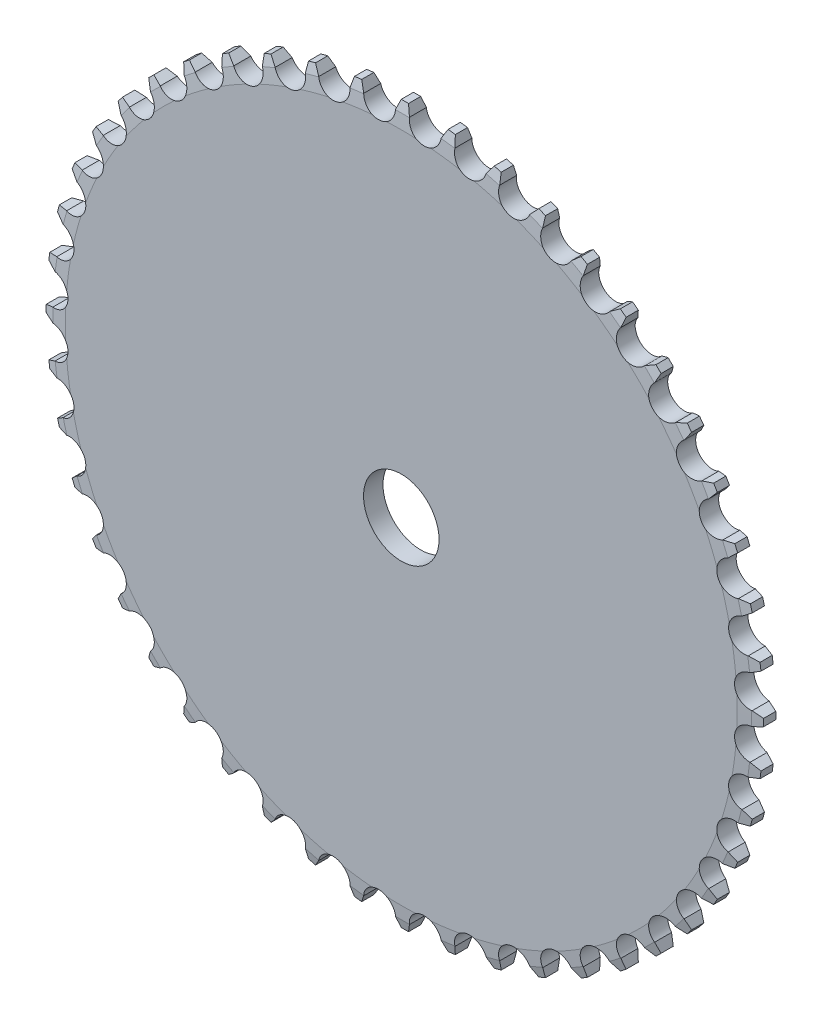
SolidWorks part; units mm, degrees
material "AISI 1045 Steel, cold drawn"
ref_plane "Front Plane" through (0, 0, 0) normal (0, 0, 1) x (1, 0, 0)
ref_plane "Top Plane" through (0, 0, 0) normal (0, 1, 0) x (1, 0, 0)
ref_plane "Right Plane" through (0, 0, 0) normal (1, 0, 0) x (0, 0, -1)
sketch "Sketch1" plane through (0, 0, 0) normal (0, 0, 1) x (1, 0, 0)
  line L0 (0, 0) -> (-4.5942, 70.0933) construction
  line L1 (0, 0) -> (4.5942, 70.0933) construction
  line L2 (0, 0) -> (0, 75.4253) construction
  line L3 (-0.762, 75.4215) -> (0.762, 75.4215)
  line L4 (0.762, 75.4215) -> (1.457, 73.512)
  line L5 (9.089, 74.8757) -> (8.1507, 73.0733)
  line L6 (18.7845, 73.0487) -> (17.619, 71.3842)
  line L7 (10.6, 74.6767) -> (11.0398, 72.6929)
  line L8 (9.089, 74.8757) -> (10.6, 74.6767)
  line L9 (28.1585, 69.9719) -> (26.7857, 68.4738)
  line L10 (20.2565, 72.6543) -> (20.4336, 70.63)
  line L11 (18.7845, 73.0487) -> (20.2565, 72.6543)
  line L12 (37.0508, 65.6979) -> (35.4942, 64.3917)
  line L13 (29.5665, 69.3887) -> (29.4779, 67.3587)
  line L14 (28.1585, 69.9719) -> (29.5665, 69.3887)
  line L15 (45.3091, 60.2997) -> (43.5954, 59.2079)
  line L16 (38.3706, 64.9359) -> (38.0178, 62.9348)
  line L17 (37.0508, 65.6979) -> (38.3706, 64.9359)
  line L18 (52.7922, 53.8698) -> (50.9506, 53.0111)
  line L19 (46.5182, 59.372) -> (45.9072, 57.434)
  line L20 (45.3091, 60.2997) -> (46.5182, 59.372)
  line L21 (59.372, 46.5182) -> (57.434, 45.9072)
  line L22 (53.8698, 52.7922) -> (53.0111, 50.9506)
  line L23 (52.7922, 53.8698) -> (53.8698, 52.7922)
  line L24 (64.9359, 38.3706) -> (62.9348, 38.0178)
  line L25 (60.2997, 45.3091) -> (59.2079, 43.5954)
  line L26 (59.372, 46.5182) -> (60.2997, 45.3091)
  line L27 (69.3887, 29.5665) -> (67.3587, 29.4779)
  line L28 (65.6979, 37.0508) -> (64.3917, 35.4942)
  line L29 (64.9359, 38.3706) -> (65.6979, 37.0508)
  line L30 (72.6543, 20.2565) -> (70.63, 20.4336)
  line L31 (69.9719, 28.1585) -> (68.4738, 26.7857)
  line L32 (69.3887, 29.5665) -> (69.9719, 28.1585)
  line L33 (74.6767, 10.6) -> (72.6929, 11.0398)
  line L34 (73.0487, 18.7845) -> (71.3842, 17.619)
  line L35 (72.6543, 20.2565) -> (73.0487, 18.7845)
  line L36 (75.4215, 0.762) -> (73.512, 1.457)
  line L37 (74.8757, 9.089) -> (73.0733, 8.1507)
  line L38 (74.6767, 10.6) -> (74.8757, 9.089)
  line L39 (74.8757, -9.089) -> (73.0733, -8.1507)
  line L40 (75.4215, -0.762) -> (73.512, -1.457)
  line L41 (75.4215, 0.762) -> (75.4215, -0.762)
  line L42 (73.0487, -18.7845) -> (71.3842, -17.619)
  line L43 (74.6767, -10.6) -> (72.6929, -11.0398)
  line L44 (74.8757, -9.089) -> (74.6767, -10.6)
  line L45 (69.9719, -28.1585) -> (68.4738, -26.7857)
  line L46 (72.6543, -20.2565) -> (70.63, -20.4336)
  line L47 (73.0487, -18.7845) -> (72.6543, -20.2565)
  line L48 (65.6979, -37.0508) -> (64.3917, -35.4942)
  line L49 (69.3887, -29.5665) -> (67.3587, -29.4779)
  line L50 (69.9719, -28.1585) -> (69.3887, -29.5665)
  line L51 (60.2997, -45.3091) -> (59.2079, -43.5954)
  line L52 (64.9359, -38.3706) -> (62.9348, -38.0178)
  line L53 (65.6979, -37.0508) -> (64.9359, -38.3706)
  line L54 (53.8698, -52.7922) -> (53.0111, -50.9506)
  line L55 (59.372, -46.5182) -> (57.434, -45.9072)
  line L56 (60.2997, -45.3091) -> (59.372, -46.5182)
  line L57 (46.5182, -59.372) -> (45.9072, -57.434)
  line L58 (52.7922, -53.8698) -> (50.9506, -53.0111)
  line L59 (53.8698, -52.7922) -> (52.7922, -53.8698)
  line L60 (38.3706, -64.9359) -> (38.0178, -62.9348)
  line L61 (45.3091, -60.2997) -> (43.5954, -59.2079)
  line L62 (46.5182, -59.372) -> (45.3091, -60.2997)
  line L63 (29.5665, -69.3887) -> (29.4779, -67.3587)
  line L64 (37.0508, -65.6979) -> (35.4942, -64.3917)
  line L65 (38.3706, -64.9359) -> (37.0508, -65.6979)
  line L66 (20.2565, -72.6543) -> (20.4336, -70.63)
  line L67 (28.1585, -69.9719) -> (26.7857, -68.4738)
  line L68 (29.5665, -69.3887) -> (28.1585, -69.9719)
  line L69 (10.6, -74.6767) -> (11.0398, -72.6929)
  line L70 (18.7845, -73.0487) -> (17.619, -71.3842)
  line L71 (20.2565, -72.6543) -> (18.7845, -73.0487)
  line L72 (0.762, -75.4215) -> (1.457, -73.512)
  line L73 (9.089, -74.8757) -> (8.1507, -73.0733)
  line L74 (10.6, -74.6767) -> (9.089, -74.8757)
  line L75 (-9.089, -74.8757) -> (-8.1507, -73.0733)
  line L76 (-0.762, -75.4215) -> (-1.457, -73.512)
  line L77 (0.762, -75.4215) -> (-0.762, -75.4215)
  line L78 (-18.7845, -73.0487) -> (-17.619, -71.3842)
  line L79 (-10.6, -74.6767) -> (-11.0398, -72.6929)
  line L80 (-9.089, -74.8757) -> (-10.6, -74.6767)
  line L81 (-28.1585, -69.9719) -> (-26.7857, -68.4738)
  line L82 (-20.2565, -72.6543) -> (-20.4336, -70.63)
  line L83 (-18.7845, -73.0487) -> (-20.2565, -72.6543)
  line L84 (-37.0508, -65.6979) -> (-35.4942, -64.3917)
  line L85 (-29.5665, -69.3887) -> (-29.4779, -67.3587)
  line L86 (-28.1585, -69.9719) -> (-29.5665, -69.3887)
  line L87 (-45.3091, -60.2997) -> (-43.5954, -59.2079)
  line L88 (-38.3706, -64.9359) -> (-38.0178, -62.9348)
  line L89 (-37.0508, -65.6979) -> (-38.3706, -64.9359)
  line L90 (-52.7922, -53.8698) -> (-50.9506, -53.0111)
  line L91 (-46.5182, -59.372) -> (-45.9072, -57.434)
  line L92 (-45.3091, -60.2997) -> (-46.5182, -59.372)
  line L93 (-59.372, -46.5182) -> (-57.434, -45.9072)
  line L94 (-53.8698, -52.7922) -> (-53.0111, -50.9506)
  line L95 (-52.7922, -53.8698) -> (-53.8698, -52.7922)
  line L96 (-64.9359, -38.3706) -> (-62.9348, -38.0178)
  line L97 (-60.2997, -45.3091) -> (-59.2079, -43.5954)
  line L98 (-59.372, -46.5182) -> (-60.2997, -45.3091)
  line L99 (-69.3887, -29.5665) -> (-67.3587, -29.4779)
  line L100 (-65.6979, -37.0508) -> (-64.3917, -35.4942)
  line L101 (-64.9359, -38.3706) -> (-65.6979, -37.0508)
  line L102 (-72.6543, -20.2565) -> (-70.63, -20.4336)
  line L103 (-69.9719, -28.1585) -> (-68.4738, -26.7857)
  line L104 (-69.3887, -29.5665) -> (-69.9719, -28.1585)
  line L105 (-74.6767, -10.6) -> (-72.6929, -11.0398)
  line L106 (-73.0487, -18.7845) -> (-71.3842, -17.619)
  line L107 (-72.6543, -20.2565) -> (-73.0487, -18.7845)
  line L108 (-75.4215, -0.762) -> (-73.512, -1.457)
  line L109 (-74.8757, -9.089) -> (-73.0733, -8.1507)
  line L110 (-74.6767, -10.6) -> (-74.8757, -9.089)
  line L111 (-74.8757, 9.089) -> (-73.0733, 8.1507)
  line L112 (-75.4215, 0.762) -> (-73.512, 1.457)
  line L113 (-75.4215, -0.762) -> (-75.4215, 0.762)
  line L114 (-73.0487, 18.7845) -> (-71.3842, 17.619)
  line L115 (-74.6767, 10.6) -> (-72.6929, 11.0398)
  line L116 (-74.8757, 9.089) -> (-74.6767, 10.6)
  line L117 (-69.9719, 28.1585) -> (-68.4738, 26.7857)
  line L118 (-72.6543, 20.2565) -> (-70.63, 20.4336)
  line L119 (-73.0487, 18.7845) -> (-72.6543, 20.2565)
  line L120 (-65.6979, 37.0508) -> (-64.3917, 35.4942)
  line L121 (-69.3887, 29.5665) -> (-67.3587, 29.4779)
  line L122 (-69.9719, 28.1585) -> (-69.3887, 29.5665)
  line L123 (-60.2997, 45.3091) -> (-59.2079, 43.5954)
  line L124 (-64.9359, 38.3706) -> (-62.9348, 38.0178)
  line L125 (-65.6979, 37.0508) -> (-64.9359, 38.3706)
  line L126 (-53.8698, 52.7922) -> (-53.0111, 50.9506)
  line L127 (-59.372, 46.5182) -> (-57.434, 45.9072)
  line L128 (-60.2997, 45.3091) -> (-59.372, 46.5182)
  line L129 (-46.5182, 59.372) -> (-45.9072, 57.434)
  line L130 (-52.7922, 53.8698) -> (-50.9506, 53.0111)
  line L131 (-53.8698, 52.7922) -> (-52.7922, 53.8698)
  line L132 (-38.3706, 64.9359) -> (-38.0178, 62.9348)
  line L133 (-45.3091, 60.2997) -> (-43.5954, 59.2079)
  line L134 (-46.5182, 59.372) -> (-45.3091, 60.2997)
  line L135 (-29.5665, 69.3887) -> (-29.4779, 67.3587)
  line L136 (-37.0508, 65.6979) -> (-35.4942, 64.3917)
  line L137 (-38.3706, 64.9359) -> (-37.0508, 65.6979)
  line L138 (-20.2565, 72.6543) -> (-20.4336, 70.63)
  line L139 (-28.1585, 69.9719) -> (-26.7857, 68.4738)
  line L140 (-29.5665, 69.3887) -> (-28.1585, 69.9719)
  line L141 (-10.6, 74.6767) -> (-11.0398, 72.6929)
  line L142 (-18.7845, 73.0487) -> (-17.619, 71.3842)
  line L143 (-20.2565, 72.6543) -> (-18.7845, 73.0487)
  line L144 (-0.762, 75.4215) -> (-1.457, 73.512)
  line L145 (-9.089, 74.8757) -> (-8.1507, 73.0733)
  line L146 (-10.6, 74.6767) -> (-9.089, 74.8757)
  circle A0 centre (0, 0) radius 75.4253 construction
  circle A1 centre (0, 0) radius 70.2437 construction
  circle A2 centre (0, 0) radius 7.9375
  circle A3 centre (0, 0) radius 73.5264 construction
  arc A4 (1.457, 73.512) -> (4.5942, 70.0933) centre (4.8137, 73.4436) ccw
  arc A5 (4.5942, 70.0933) -> (8.1507, 73.0733) centre (4.8137, 73.4436) ccw
  arc A6 (13.7039, 68.894) -> (17.619, 71.3842) centre (14.3589, 72.1869) ccw
  arc A7 (11.0398, 72.6929) -> (13.7039, 68.894) centre (14.3589, 72.1869) ccw
  arc A8 (22.5791, 66.5159) -> (26.7857, 68.4738) centre (23.6583, 69.6952) ccw
  arc A9 (20.4336, 70.63) -> (22.5791, 66.5159) centre (23.6583, 69.6952) ccw
  arc A10 (31.068, 62.9997) -> (35.4942, 64.3917) centre (32.553, 66.0109) ccw
  arc A11 (29.4779, 67.3587) -> (31.068, 62.9997) centre (32.553, 66.0109) ccw
  arc A12 (39.0253, 58.4055) -> (43.5954, 59.2079) centre (40.8906, 61.1971) ccw
  arc A13 (38.0178, 62.9348) -> (39.0253, 58.4055) centre (40.8906, 61.1971) ccw
  arc A14 (46.3149, 52.812) -> (50.9506, 53.0111) centre (48.5286, 55.3363) ccw
  arc A15 (45.9072, 57.434) -> (46.3149, 52.812) centre (48.5286, 55.3363) ccw
  arc A16 (52.812, 46.3149) -> (57.434, 45.9072) centre (55.3363, 48.5286) ccw
  arc A17 (53.0111, 50.9506) -> (52.812, 46.3149) centre (55.3363, 48.5286) ccw
  arc A18 (58.4055, 39.0253) -> (62.9348, 38.0178) centre (61.1971, 40.8906) ccw
  arc A19 (59.2079, 43.5954) -> (58.4055, 39.0253) centre (61.1971, 40.8906) ccw
  arc A20 (62.9997, 31.068) -> (67.3587, 29.4779) centre (66.0109, 32.553) ccw
  arc A21 (64.3917, 35.4942) -> (62.9997, 31.068) centre (66.0109, 32.553) ccw
  arc A22 (66.5159, 22.5791) -> (70.63, 20.4336) centre (69.6952, 23.6583) ccw
  arc A23 (68.4738, 26.7857) -> (66.5159, 22.5791) centre (69.6952, 23.6583) ccw
  arc A24 (68.894, 13.7039) -> (72.6929, 11.0398) centre (72.1869, 14.3589) ccw
  arc A25 (71.3842, 17.619) -> (68.894, 13.7039) centre (72.1869, 14.3589) ccw
  arc A26 (70.0933, 4.5942) -> (73.512, 1.457) centre (73.4436, 4.8137) ccw
  arc A27 (73.0733, 8.1507) -> (70.0933, 4.5942) centre (73.4436, 4.8137) ccw
  arc A28 (70.0933, -4.5942) -> (73.0733, -8.1507) centre (73.4436, -4.8137) ccw
  arc A29 (73.512, -1.457) -> (70.0933, -4.5942) centre (73.4436, -4.8137) ccw
  arc A30 (68.894, -13.7039) -> (71.3842, -17.619) centre (72.1869, -14.3589) ccw
  arc A31 (72.6929, -11.0398) -> (68.894, -13.7039) centre (72.1869, -14.3589) ccw
  arc A32 (66.5159, -22.5791) -> (68.4738, -26.7857) centre (69.6952, -23.6583) ccw
  arc A33 (70.63, -20.4336) -> (66.5159, -22.5791) centre (69.6952, -23.6583) ccw
  arc A34 (62.9997, -31.068) -> (64.3917, -35.4942) centre (66.0109, -32.553) ccw
  arc A35 (67.3587, -29.4779) -> (62.9997, -31.068) centre (66.0109, -32.553) ccw
  arc A36 (58.4055, -39.0253) -> (59.2079, -43.5954) centre (61.1971, -40.8906) ccw
  arc A37 (62.9348, -38.0178) -> (58.4055, -39.0253) centre (61.1971, -40.8906) ccw
  arc A38 (52.812, -46.3149) -> (53.0111, -50.9506) centre (55.3363, -48.5286) ccw
  arc A39 (57.434, -45.9072) -> (52.812, -46.3149) centre (55.3363, -48.5286) ccw
  arc A40 (46.3149, -52.812) -> (45.9072, -57.434) centre (48.5286, -55.3363) ccw
  arc A41 (50.9506, -53.0111) -> (46.3149, -52.812) centre (48.5286, -55.3363) ccw
  arc A42 (39.0253, -58.4055) -> (38.0178, -62.9348) centre (40.8906, -61.1971) ccw
  arc A43 (43.5954, -59.2079) -> (39.0253, -58.4055) centre (40.8906, -61.1971) ccw
  arc A44 (31.068, -62.9997) -> (29.4779, -67.3587) centre (32.553, -66.0109) ccw
  arc A45 (35.4942, -64.3917) -> (31.068, -62.9997) centre (32.553, -66.0109) ccw
  arc A46 (22.5791, -66.5159) -> (20.4336, -70.63) centre (23.6583, -69.6952) ccw
  arc A47 (26.7857, -68.4738) -> (22.5791, -66.5159) centre (23.6583, -69.6952) ccw
  arc A48 (13.7039, -68.894) -> (11.0398, -72.6929) centre (14.3589, -72.1869) ccw
  arc A49 (17.619, -71.3842) -> (13.7039, -68.894) centre (14.3589, -72.1869) ccw
  arc A50 (4.5942, -70.0933) -> (1.457, -73.512) centre (4.8137, -73.4436) ccw
  arc A51 (8.1507, -73.0733) -> (4.5942, -70.0933) centre (4.8137, -73.4436) ccw
  arc A52 (-4.5942, -70.0933) -> (-8.1507, -73.0733) centre (-4.8137, -73.4436) ccw
  arc A53 (-1.457, -73.512) -> (-4.5942, -70.0933) centre (-4.8137, -73.4436) ccw
  arc A54 (-13.7039, -68.894) -> (-17.619, -71.3842) centre (-14.3589, -72.1869) ccw
  arc A55 (-11.0398, -72.6929) -> (-13.7039, -68.894) centre (-14.3589, -72.1869) ccw
  arc A56 (-22.5791, -66.5159) -> (-26.7857, -68.4738) centre (-23.6583, -69.6952) ccw
  arc A57 (-20.4336, -70.63) -> (-22.5791, -66.5159) centre (-23.6583, -69.6952) ccw
  arc A58 (-31.068, -62.9997) -> (-35.4942, -64.3917) centre (-32.553, -66.0109) ccw
  arc A59 (-29.4779, -67.3587) -> (-31.068, -62.9997) centre (-32.553, -66.0109) ccw
  arc A60 (-39.0253, -58.4055) -> (-43.5954, -59.2079) centre (-40.8906, -61.1971) ccw
  arc A61 (-38.0178, -62.9348) -> (-39.0253, -58.4055) centre (-40.8906, -61.1971) ccw
  arc A62 (-46.3149, -52.812) -> (-50.9506, -53.0111) centre (-48.5286, -55.3363) ccw
  arc A63 (-45.9072, -57.434) -> (-46.3149, -52.812) centre (-48.5286, -55.3363) ccw
  arc A64 (-52.812, -46.3149) -> (-57.434, -45.9072) centre (-55.3363, -48.5286) ccw
  arc A65 (-53.0111, -50.9506) -> (-52.812, -46.3149) centre (-55.3363, -48.5286) ccw
  arc A66 (-58.4055, -39.0253) -> (-62.9348, -38.0178) centre (-61.1971, -40.8906) ccw
  arc A67 (-59.2079, -43.5954) -> (-58.4055, -39.0253) centre (-61.1971, -40.8906) ccw
  arc A68 (-62.9997, -31.068) -> (-67.3587, -29.4779) centre (-66.0109, -32.553) ccw
  arc A69 (-64.3917, -35.4942) -> (-62.9997, -31.068) centre (-66.0109, -32.553) ccw
  arc A70 (-66.5159, -22.5791) -> (-70.63, -20.4336) centre (-69.6952, -23.6583) ccw
  arc A71 (-68.4738, -26.7857) -> (-66.5159, -22.5791) centre (-69.6952, -23.6583) ccw
  arc A72 (-68.894, -13.7039) -> (-72.6929, -11.0398) centre (-72.1869, -14.3589) ccw
  arc A73 (-71.3842, -17.619) -> (-68.894, -13.7039) centre (-72.1869, -14.3589) ccw
  arc A74 (-70.0933, -4.5942) -> (-73.512, -1.457) centre (-73.4436, -4.8137) ccw
  arc A75 (-73.0733, -8.1507) -> (-70.0933, -4.5942) centre (-73.4436, -4.8137) ccw
  arc A76 (-70.0933, 4.5942) -> (-73.0733, 8.1507) centre (-73.4436, 4.8137) ccw
  arc A77 (-73.512, 1.457) -> (-70.0933, 4.5942) centre (-73.4436, 4.8137) ccw
  arc A78 (-68.894, 13.7039) -> (-71.3842, 17.619) centre (-72.1869, 14.3589) ccw
  arc A79 (-72.6929, 11.0398) -> (-68.894, 13.7039) centre (-72.1869, 14.3589) ccw
  arc A80 (-66.5159, 22.5791) -> (-68.4738, 26.7857) centre (-69.6952, 23.6583) ccw
  arc A81 (-70.63, 20.4336) -> (-66.5159, 22.5791) centre (-69.6952, 23.6583) ccw
  arc A82 (-62.9997, 31.068) -> (-64.3917, 35.4942) centre (-66.0109, 32.553) ccw
  arc A83 (-67.3587, 29.4779) -> (-62.9997, 31.068) centre (-66.0109, 32.553) ccw
  arc A84 (-58.4055, 39.0253) -> (-59.2079, 43.5954) centre (-61.1971, 40.8906) ccw
  arc A85 (-62.9348, 38.0178) -> (-58.4055, 39.0253) centre (-61.1971, 40.8906) ccw
  arc A86 (-52.812, 46.3149) -> (-53.0111, 50.9506) centre (-55.3363, 48.5286) ccw
  arc A87 (-57.434, 45.9072) -> (-52.812, 46.3149) centre (-55.3363, 48.5286) ccw
  arc A88 (-46.3149, 52.812) -> (-45.9072, 57.434) centre (-48.5286, 55.3363) ccw
  arc A89 (-50.9506, 53.0111) -> (-46.3149, 52.812) centre (-48.5286, 55.3363) ccw
  arc A90 (-39.0253, 58.4055) -> (-38.0178, 62.9348) centre (-40.8906, 61.1971) ccw
  arc A91 (-43.5954, 59.2079) -> (-39.0253, 58.4055) centre (-40.8906, 61.1971) ccw
  arc A92 (-31.068, 62.9997) -> (-29.4779, 67.3587) centre (-32.553, 66.0109) ccw
  arc A93 (-35.4942, 64.3917) -> (-31.068, 62.9997) centre (-32.553, 66.0109) ccw
  arc A94 (-22.5791, 66.5159) -> (-20.4336, 70.63) centre (-23.6583, 69.6952) ccw
  arc A95 (-26.7857, 68.4738) -> (-22.5791, 66.5159) centre (-23.6583, 69.6952) ccw
  arc A96 (-13.7039, 68.894) -> (-11.0398, 72.6929) centre (-14.3589, 72.1869) ccw
  arc A97 (-17.619, 71.3842) -> (-13.7039, 68.894) centre (-14.3589, 72.1869) ccw
  arc A98 (-4.5942, 70.0933) -> (-1.457, 73.512) centre (-4.8137, 73.4436) ccw
  arc A99 (-8.1507, 73.0733) -> (-4.5942, 70.0933) centre (-4.8137, 73.4436) ccw
  point P11 (0, 75.4215)
  point P14 (0, 73.5264)
  dimension "D1" = 150.8506
  dimension "D2" = 140.4874
  dimension "D3" = 15.875
  dimension "D6" = 1.524
  dimension "D8" = 2.032
  dimension "D7" = 48
  dimension "D4" = 7.5
  dimension "D5" = 3.75
  dimension "D10" = 110
extrude "Boss-Extrude2" add sketch "Sketch1" along normal blind 4.0894 contours A99 L145 L146 L141 A96 A97 L142 L143 L138 A94 A95 L139 L140 L135 A92 A93 L136 L137 L132 A90 A91 L133 L134 L129 A88 A89 L130 L131 L126 A86 A87 L127 L128 L123 A84 A85 L124 L125 L120 A82 A83 L121 L122 L117 A80 A81 L118 L119 L114 A78 A79
sketch "Sketch3" plane through (0, 0, 0) normal (1, 0, 0) x (0, 0, -1)
  line L0 (-3.3274, 75.4215) -> (-3.8487, 73.4575)
  line L1 (-4.0894, 75.4215) -> (0, 75.4215) construction
  line L2 (-3.8487, 73.4575) -> (-4.0894, 70.63)
  line L6 (-2.0447, 75.4215) -> (-2.0447, 71.5759) construction
  line L11 (-3.3274, 75.4215) -> (-3.3274, 76.3648)
  line L12 (-3.3274, 76.3648) -> (-4.7523, 76.3648)
  line L13 (-4.7523, 76.3648) -> (-4.7523, 70.63)
  line L14 (-4.7523, 70.63) -> (-4.0894, 70.63)
  line L15 (0.6629, 70.63) -> (0, 70.63)
  line L16 (0.6629, 76.3648) -> (0.6629, 70.63)
  line L17 (-0.762, 76.3648) -> (0.6629, 76.3648)
  line L18 (-0.762, 75.4215) -> (-0.762, 76.3648)
  line L19 (-0.2407, 73.4575) -> (0, 70.63)
  line L20 (-0.762, 75.4215) -> (-0.2407, 73.4575)
  point P7 (-2.0447, 75.4215)
  dimension "D1" = 2.032
  dimension "D2" = 170
  dimension "D3" = 0.762
ref_axis "Axis1" through (0, 0, 4.0894) along (0, 0, -1)
revolve "Cut-Revolve3" cut sketch "Sketch3" angle 360 about axis through (0, 0, 4.0894) along (0, 0, -1)
